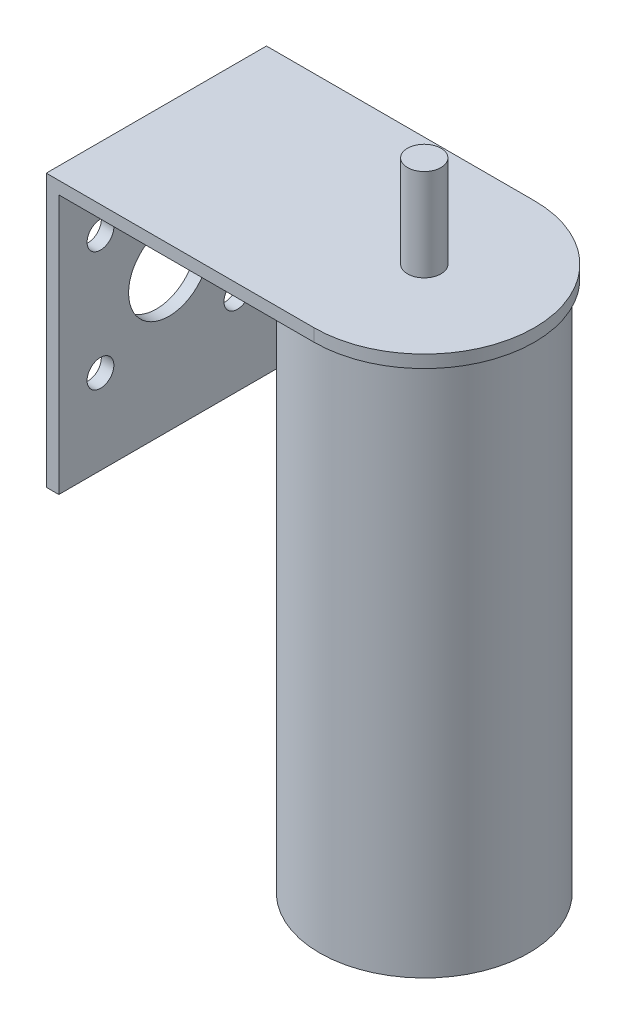
SolidWorks part; units mm, degrees
ref_plane "Front Plane" through (0, 0, 0) normal (0, 0, 1) x (1, 0, 0)
ref_plane "Top Plane" through (0, 0, 0) normal (0, 1, 0) x (1, 0, 0)
ref_plane "Right Plane" through (0, 0, 0) normal (1, 0, 0) x (0, 0, -1)
sketch "Sketch1" plane through (0, 0, 0) normal (0, 1, 0) x (1, 0, 0)
  circle A0 centre (0, 0) radius 12.5
  dimension "D1" = 25
extrude "Boss-Extrude1" add sketch "Sketch1" along normal blind 65
sketch "Sketch3" plane through (0, 65, 0) normal (0, 1, 0) x (1, 0, 0)
  circle A0 centre (0, 0) radius 2
  dimension "D1" = 4
extrude "Boss-Extrude2" add sketch "Sketch3" along normal blind 11
sketch "Sketch4" plane through (0, 65, 0) normal (0, 1, 0) x (1, 0, 0)
  line L0 (0, 0) -> (-32, 0) construction
  line L1 (0, 13.15) -> (0, -13.15) construction
  line L2 (0, 13.15) -> (-32, 13.15)
  line L3 (-32, 13.15) -> (-32, -13.15)
  line L4 (-32, -13.15) -> (0, -13.15)
  arc A0 (0, 13.15) -> (0, -13.15) centre (0, 0) cw
  point P6 (0, 0)
  dimension "D1" = 32
  dimension "D2" = 26.3
extrude "Boss-Extrude3" add sketch "Sketch4" against normal blind 1.5 contours L4 A0 L2 L3
sketch "Sketch5" plane through (0, 63.5, 0) normal (0, -1, 0) x (1, 0, 0)
  line L0 (0, -13.15) -> (-32, -13.15) construction
  line L1 (-32, 13.15) -> (-30.5, 13.15)
  line L2 (-32, 13.15) -> (-32, -13.15)
  line L3 (-32, -13.15) -> (-30.5, -13.15)
  line L4 (-30.5, 13.15) -> (-30.5, -13.15)
  dimension "D1" = 1.5
extrude "Boss-Extrude4" add sketch "Sketch5" along normal blind 31
sketch "Sketch6" plane through (-32, 0, 0) normal (-1, 0, 0) x (0, 0, 1)
  line L0 (0, 65) -> (0, 32.5) construction
  line L3 (-13.15, 65) -> (13.15, 65) construction
  line L4 (13.15, 32.5) -> (-13.15, 32.5) construction
  line L5 (0, 32.5) -> (0, 48.75) construction
  line L6 (0, 54) -> (0, 65) construction
  line L7 (8.175, 58.5) -> (8.175, 65) construction
  line L8 (-8.175, 42.6) -> (8.175, 42.6) construction
  line L9 (-8.175, 42.6) -> (-8.175, 56.9) construction
  line L10 (-8.175, 56.9) -> (8.175, 56.9) construction
  line L11 (8.175, 42.6) -> (8.175, 56.9) construction
  line L12 (-8.175, 42.6) -> (8.175, 56.9) construction
  line L13 (-8.175, 56.9) -> (8.175, 42.6) construction
  line L14 (-9.775, 56.9) -> (9.775, 56.9) construction
  line L15 (-8.175, 58.5) -> (-8.175, 41) construction
  circle A0 centre (0, 49.1813) radius 4.8187
  circle A1 centre (-8.175, 56.9) radius 1.6
  circle A2 centre (8.175, 56.9) radius 1.6
  circle A3 centre (8.175, 42.6) radius 1.6
  circle A4 centre (-8.175, 42.6) radius 1.6
  point P3 (0, 65)
  point P25 (0, 0)
  point P26 (0, 0)
  point P27 (0, 49.75)
  dimension "D3" = 3.2
  dimension "D4" = 19.55
  dimension "D1" = 11
  dimension "D2" = 6.5
  dimension "D5" = 17.5
extrude "Cut-Extrude1" cut sketch "Sketch6" against normal blind 11
sketch "Sketch7" plane through (-32, 0, 0) normal (-1, 0, 0) x (0, 0, 1)
  line L0 (-8.175, 56.9) -> (8.175, 42.6) construction
  line L1 (8.175, 42.6) -> (8.175, 56.9) construction
  line L2 (8.175, 56.9) -> (0, 56.9) construction
  line L3 (0, 56.9) -> (0, 49.75) construction
  line L4 (-8.175, 56.9) -> (8.175, 56.9) construction
  dimension "D1" = 21.7212
  dimension "D2" = 14.3
  dimension "D3" = 16.35
